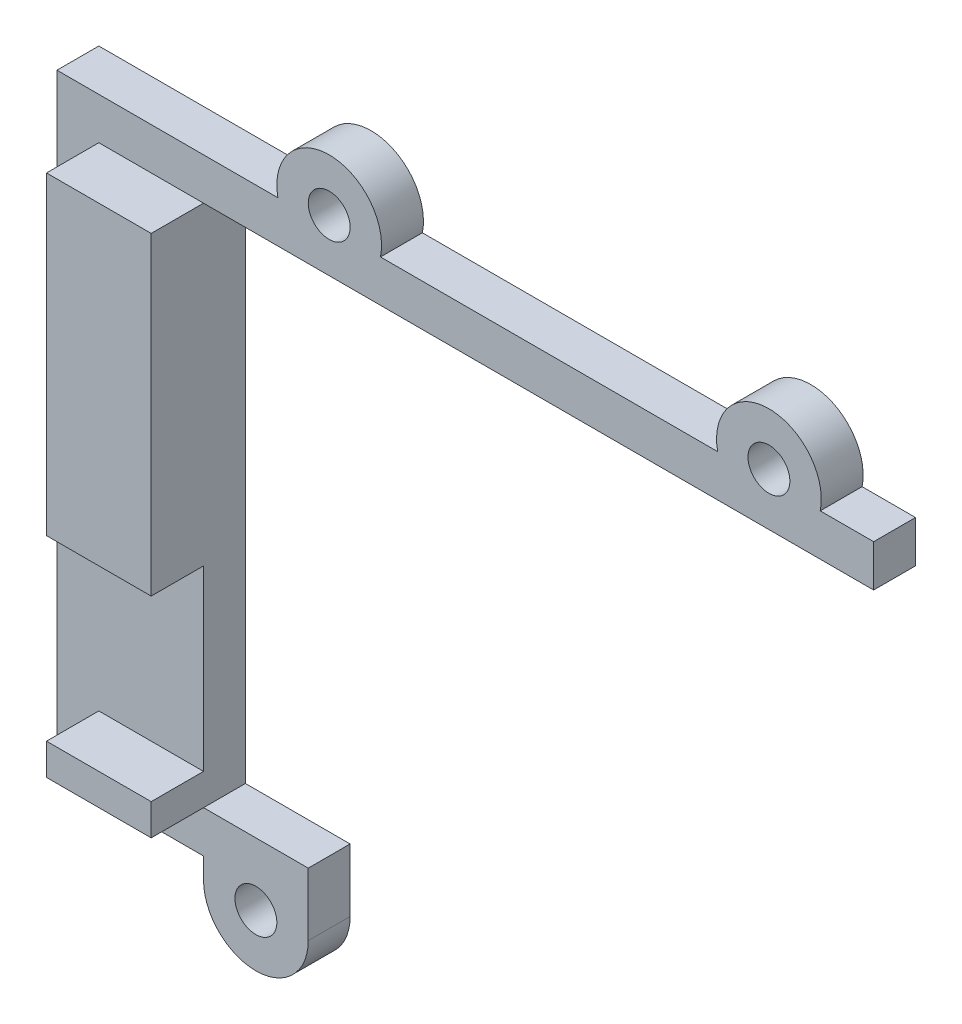
SolidWorks part; units mm, degrees
ref_plane "Front Plane" through (0, 0, 0) normal (0, 0, 1) x (1, 0, 0)
ref_plane "Top Plane" through (0, 0, 0) normal (0, 1, 0) x (1, 0, 0)
ref_plane "Right Plane" through (0, 0, 0) normal (1, 0, 0) x (0, 0, -1)
sketch "Sketch1" plane through (0, 0, -7) normal (0, 0, -1) x (-1, 0, 0)
  line L0 (15.5, 18) -> (15.5, 40) construction
  line L1 (21.5, 41.5) -> (16.5, 41.5)
  line L2 (21.5, 41.5) -> (21.5, 26.5)
  line L3 (21.5, 26.5) -> (16.5, 26.5)
  line L4 (16.5, 41.5) -> (16.5, 26.5)
  line L5 (21.5, 26.5) -> (23.5, 26.5) construction
  line L6 (23.5, 18) -> (21.5, 18) construction
  line L7 (21.5, 16.5) -> (16.5, 16.5)
  line L8 (21.5, 16.5) -> (21.5, 18)
  line L9 (21.5, 18) -> (16.5, 18)
  line L10 (16.5, 16.5) -> (16.5, 18)
  dimension "D1" = 1
extrude "Clamp part" add sketch "Sketch1" against normal blind 2.5
sketch "Sketch2" plane through (0, 0, -7) normal (0, 0, -1) x (-1, 0, 0)
  line L0 (-15.5, 14.5) -> (11.5, 14.5) construction
  line L1 (23.5, 43.5) -> (16.5, 43.5)
  line L2 (23.5, 43.5) -> (23.5, 14.5)
  line L3 (23.5, 14.5) -> (16.5, 14.5)
  line L4 (16.5, 41.5) -> (16.5, 16.5)
  line L5 (16.5, 41.5) -> (16.5, 26.5) construction
  line L6 (-12.9495, 43.5) -> (-15.5, 43.5) construction
  line L7 (8.0505, 43.5) -> (-8.0505, 43.5) construction
  line L8 (-12.9495, 43.5) -> (-15.5, 43.5)
  line L9 (8.0505, 43.5) -> (-8.0505, 43.5)
  line L10 (-15.5, 43.5) -> (-15.5, 41.5)
  line L11 (-15.5, 41.5) -> (16.5, 41.5)
  line L12 (16.5, 43.5) -> (12.9495, 43.5)
  line L13 (16.5, 14.5) -> (16.5, 13.5)
  line L14 (11.5, 13.5) -> (11.5, 16.5)
  line L15 (21.5, 16.5) -> (-15.5, 16.5) construction
  line L16 (11.5, 16.5) -> (16.5, 16.5)
  line L17 (23.5, 42) -> (23.5, 16) construction
  arc A0 (-8.0505, 43.5) -> (-12.9495, 43.5) centre (-10.5, 44) ccw construction
  arc A1 (12.9495, 43.5) -> (8.0505, 43.5) centre (10.5, 44) ccw construction
  arc A2 (-8.0505, 43.5) -> (-12.9495, 43.5) centre (-10.5, 44) ccw
  arc A3 (12.9495, 43.5) -> (8.0505, 43.5) centre (10.5, 44) ccw
  circle A4 centre (-10.5, 44) radius 1 construction
  circle A5 centre (10.5, 44) radius 1 construction
  circle A6 centre (-10.5, 44) radius 1
  circle A7 centre (10.5, 44) radius 1
  arc A9 (11.5, 13.5) -> (16.5, 13.5) centre (14, 13.5) ccw
  circle A11 centre (14, 13.5) radius 1 construction
  circle A12 centre (14, 13.5) radius 1
  point P28 (0, 0)
extrude "Outside" add sketch "Sketch2" along normal blind 2
